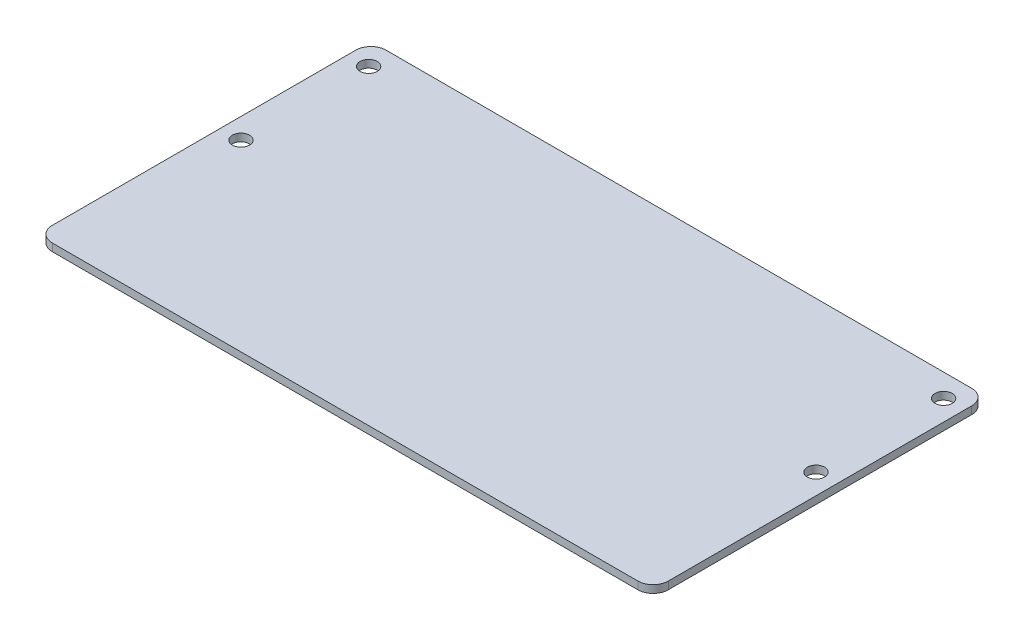
SolidWorks part; units mm, degrees
ref_plane "Plan de face" through (0, 0, 0) normal (0, 0, 1) x (1, 0, 0)
ref_plane "Plan de dessus" through (0, 0, 0) normal (0, 1, 0) x (1, 0, 0)
ref_plane "Plan de droite" through (0, 0, 0) normal (1, 0, 0) x (0, 0, -1)
sketch "Esquisse1" plane through (0, 0, 0) normal (0, 1, 0) x (1, 0, 0)
  line L1 (-60.8, 32.95) -> (60.8, 32.95)
  line L2 (-60.8, 32.95) -> (-60.8, -32.95)
  line L3 (-60.8, -32.95) -> (60.8, -32.95)
  line L4 (60.8, 32.95) -> (60.8, -32.95)
  line L5 (-60.8, 32.95) -> (60.8, -32.95) construction
  line L6 (-60.8, -32.95) -> (60.8, 32.95) construction
  point P0 (0, 0)
  dimension "D1" = 121.6
  dimension "D2" = 65.9
extrude "Boss.-Extru.1" add sketch "Esquisse1" along normal blind 1.5
fillet "Congé1" radius 3 4 edges at (60.8, 0.75, 32.95) (60.8, 0.75, -32.95) (-60.8, 0.75, -32.95) (-60.8, 0.75, 32.95)
sketch "Esquisse2" plane through (0, 1.5, 0) normal (0, 1, 0) x (1, 0, 0)
  line L0 (0, 3.25) -> (0, 0) construction
  line L1 (-56.75, 28.45) -> (56.75, 28.45) construction
  line L2 (-56.75, 28.45) -> (-56.75, 3.25) construction
  line L3 (-56.75, 3.25) -> (56.75, 3.25) construction
  line L4 (56.75, 28.45) -> (56.75, 3.25) construction
  line L5 (57.8, 32.95) -> (-57.8, 32.95) construction
  circle A0 centre (-56.75, 28.45) radius 1.7
  circle A1 centre (-56.75, 3.25) radius 1.7
  circle A2 centre (56.75, 28.45) radius 1.7
  circle A3 centre (56.75, 3.25) radius 1.7
  dimension "D4" = 3.4
  dimension "D1" = 25.2
  dimension "D2" = 113.5
  dimension "D3" = 4.5
extrude "Enlèv. mat.-Extru.1" cut sketch "Esquisse2" against normal through all
